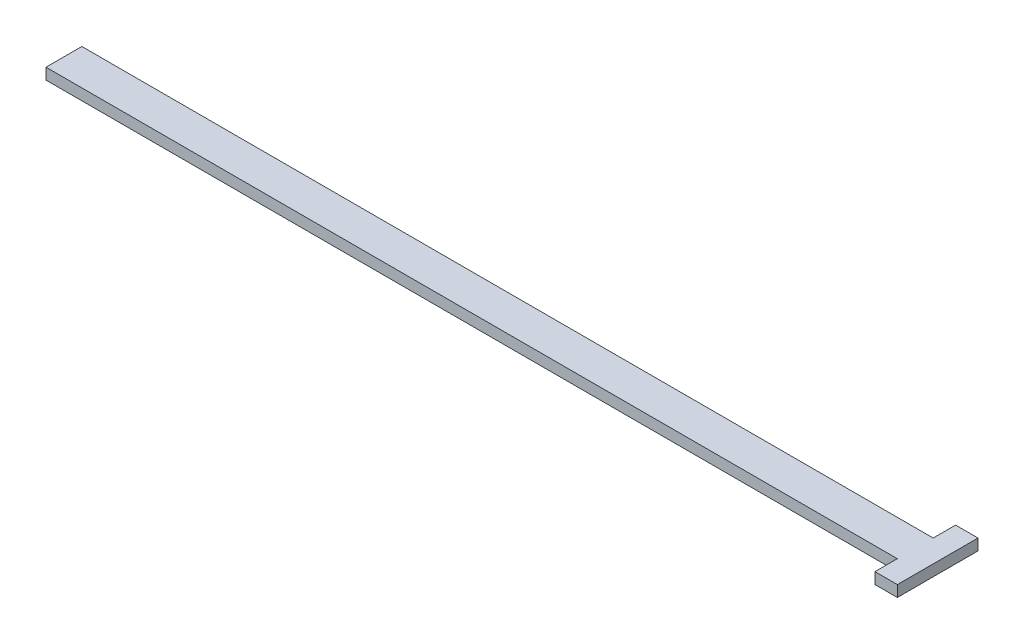
SolidWorks part; units mm, degrees
ref_plane "Front Plane" through (0, 0, 0) normal (0, 0, 1) x (1, 0, 0)
ref_plane "Top Plane" through (0, 0, 0) normal (0, 1, 0) x (1, 0, 0)
ref_plane "Right Plane" through (0, 0, 0) normal (1, 0, 0) x (0, 0, -1)
sketch "Sketch1" plane through (0, 0, 0) normal (0, 1, 0) x (1, 0, 0)
  line L1 (-123.825, 11.43) -> (123.825, 11.43)
  line L2 (-123.825, 11.43) -> (-123.825, -11.43)
  line L3 (-123.825, -11.43) -> (123.825, -11.43)
  line L4 (123.825, 11.43) -> (123.825, -11.43)
  line L5 (-123.825, 11.43) -> (123.825, -11.43) construction
  line L6 (-123.825, -11.43) -> (123.825, 11.43) construction
  point P0 (0, 0)
  dimension "D1" = 247.65
  dimension "D2" = 22.86
extrude "Boss-Extrude1" add sketch "Sketch1" along normal blind 3.175
sketch "Sketch2" plane through (0, 3.175, 0) normal (0, 1, 0) x (1, 0, 0)
  line L1 (-123.825, 11.43) -> (-117.475, 11.43)
  line L2 (-123.825, 11.43) -> (-123.825, 5.08)
  line L3 (-123.825, 5.08) -> (-117.475, 5.08)
  line L4 (-117.475, 11.43) -> (-117.475, 5.08)
  line L5 (123.825, 11.43) -> (117.475, 11.43)
  line L6 (123.825, 11.43) -> (123.825, 5.08)
  line L7 (123.825, 5.08) -> (117.475, 5.08)
  line L8 (117.475, 11.43) -> (117.475, 5.08)
  line L9 (123.825, -11.43) -> (117.475, -11.43)
  line L10 (123.825, -11.43) -> (123.825, -5.08)
  line L11 (123.825, -5.08) -> (117.475, -5.08)
  line L12 (117.475, -11.43) -> (117.475, -5.08)
  dimension "D1" = 6.35
  dimension "D2" = 6.35
extrude "Cut-Extrude1" [suppressed] cut sketch "Sketch2" against normal through all
sketch "Sketch3" plane through (0, 3.175, 0) normal (0, 1, 0) x (1, 0, 0)
  line L0 (123.825, -11.43) -> (123.825, 11.43) construction
  line L1 (-123.825, 11.43) -> (117.475, 11.43)
  line L2 (-123.825, 11.43) -> (-123.825, 5.08)
  line L3 (-123.825, 5.08) -> (117.475, 5.08)
  line L4 (117.475, 11.43) -> (117.475, 5.08)
  line L5 (-123.825, -11.43) -> (117.475, -11.43)
  line L6 (-123.825, -11.43) -> (-123.825, -5.08)
  line L7 (-123.825, -5.08) -> (117.475, -5.08)
  line L8 (117.475, -11.43) -> (117.475, -5.08)
  point P10 (0, 0)
  dimension "D1" = 6.35
  dimension "D2" = 6.35
extrude "Cut-Extrude2" cut sketch "Sketch3" against normal through all
